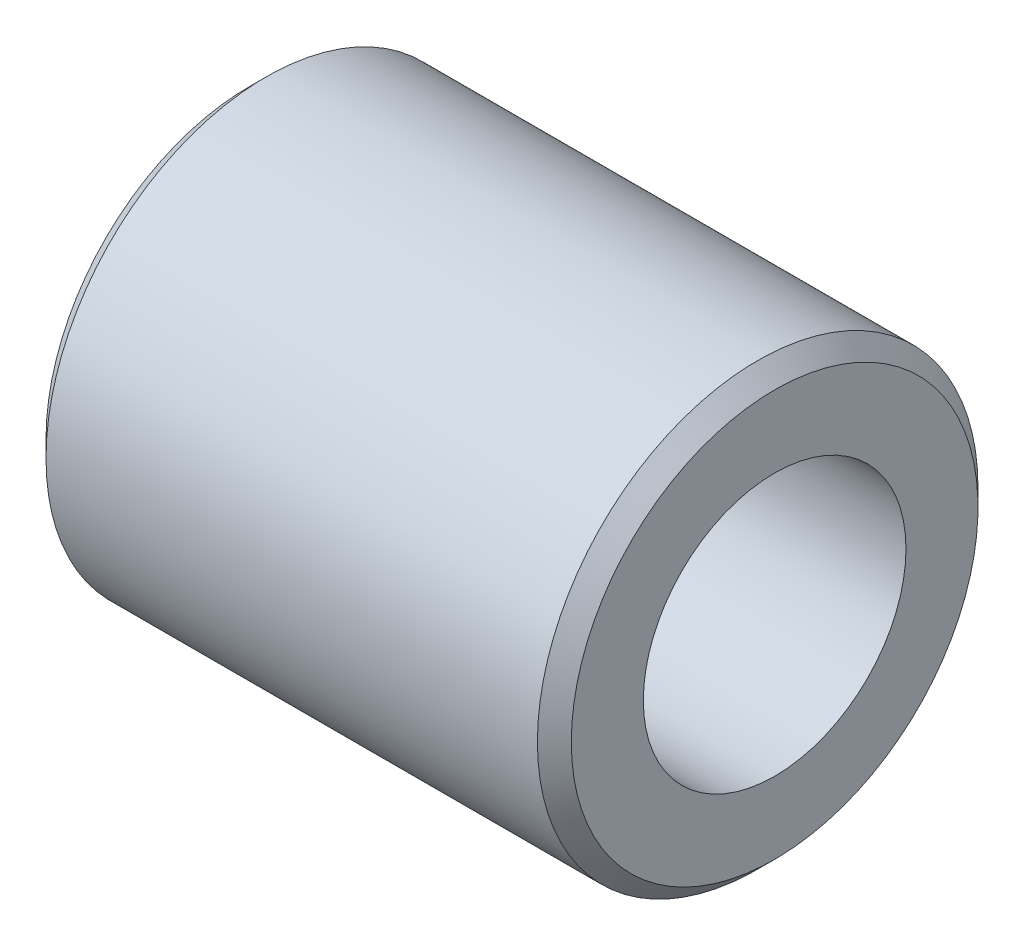
SolidWorks part; units mm, degrees
material "AISI 1020"
ref_plane "Plano frontal" through (0, 0, 0) normal (0, 0, 1) x (1, 0, 0)
ref_plane "Plano superior" through (0, 0, 0) normal (0, 1, 0) x (1, 0, 0)
ref_plane "Plano direito" through (0, 0, 0) normal (1, 0, 0) x (0, 0, -1)
sketch "Esboço1" plane through (0, 0, 0) normal (0, 0, 1) x (1, 0, 0)
  line L0 (-31, 0) -> (31, 0) construction
  line L1 (-31, 24) -> (-29, 26)
  line L2 (-31, 15.5) -> (31, 15.5)
  line L3 (-31, 15.5) -> (-31, 24)
  line L4 (-29, 26) -> (29, 26)
  line L5 (31, 15.5) -> (31, 24)
  line L6 (29, 26) -> (31, 24)
  point P4 (31, 26)
  point P5 (-31, 26)
  dimension "D1" = 31
  dimension "D2" = 52
  dimension "D3" = 62
revolve "Revolução1" add sketch "Esboço1" angle 360 about L0
